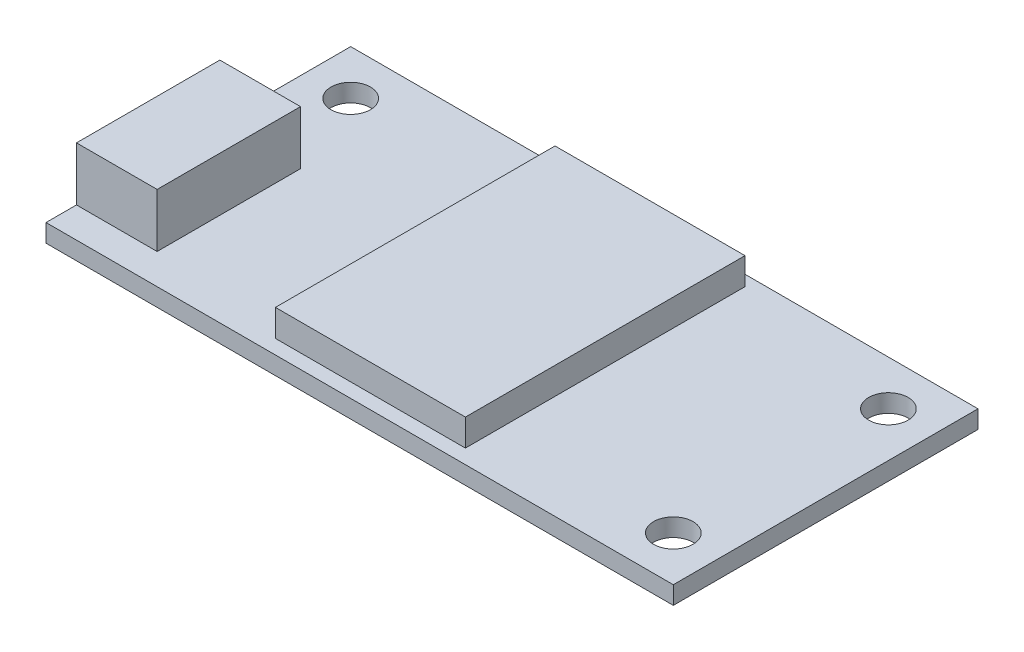
SolidWorks part; units mm, degrees
ref_plane "Front Plane" through (0, 0, 0) normal (0, 0, 1) x (1, 0, 0)
ref_plane "Top Plane" through (0, 0, 0) normal (0, 1, 0) x (1, 0, 0)
ref_plane "Right Plane" through (0, 0, 0) normal (1, 0, 0) x (0, 0, -1)
sketch "Sketch1" plane through (0, 0, 0) normal (0, 1, 0) x (1, 0, 0)
  line L1 (-17.5, -8.5) -> (17.5, -8.5)
  line L2 (-17.5, -8.5) -> (-17.5, 8.5)
  line L3 (-17.5, 8.5) -> (17.5, 8.5)
  line L4 (17.5, -8.5) -> (17.5, 8.5)
  line L5 (-17.5, -8.5) -> (17.5, 8.5) construction
  line L6 (-17.5, 8.5) -> (17.5, -8.5) construction
  point P0 (0, 0)
  dimension "D1" = 17
  dimension "D2" = 35
extrude "Boss-Extrude1" add sketch "Sketch1" along normal mid plane 1
sketch "Sketch2" plane through (0, 0.5, 0) normal (0, 1, 0) x (1, 0, 0)
  line L0 (-17.5, 8.5) -> (-17.5, -8.5) construction
  line L1 (-17.5, -6.8) -> (-13, -6.8)
  line L2 (-17.5, -6.8) -> (-17.5, 1.2)
  line L3 (-17.5, 1.2) -> (-13, 1.2)
  line L4 (-13, -6.8) -> (-13, 1.2)
  line L7 (17.5, 8.5) -> (-17.5, 8.5) construction
  dimension "D1" = 8
  dimension "D2" = 7.3
  dimension "D3" = 4.5
extrude "Boss-Extrude2" add sketch "Sketch2" along normal blind 3
sketch "Sketch3" plane through (0, 0.5, 0) normal (0, 1, 0) x (1, 0, 0)
  line L0 (-17.5, -8.5) -> (17.5, -8.5) construction
  line L1 (-5.5, -7.7) -> (5.1, -7.7)
  line L2 (-5.5, -7.7) -> (-5.5, 7.9)
  line L3 (-5.5, 7.9) -> (5.1, 7.9)
  line L4 (5.1, -7.7) -> (5.1, 7.9)
  line L5 (-17.5, 8.5) -> (-17.5, 1.2) construction
  dimension "D1" = 15.6
  dimension "D2" = 10.6
  dimension "D3" = 0.8
  dimension "D4" = 22.6
extrude "Boss-Extrude3" add sketch "Sketch3" along normal blind 1.5
sketch "Sketch4" plane through (0, 0.5, 0) normal (0, 1, 0) x (1, 0, 0)
  line L0 (-15, 6) -> (15, 6) construction
  line L1 (15, 6) -> (15, -6) construction
  line L2 (17.5, 0) -> (-17.5, 0) construction
  line L3 (17.5, -8.5) -> (17.5, 8.5) construction
  line L4 (-17.5, 1.2) -> (-17.5, -6.8) construction
  line L7 (-17.5, -8.5) -> (17.5, -8.5) construction
  line L8 (17.5, 8.5) -> (-17.5, 8.5) construction
  line L9 (-17.5, 8.5) -> (-17.5, 1.2) construction
  circle A0 centre (15, 6) radius 1.1
  circle A1 centre (15, -6) radius 1.1
  circle A2 centre (-15, 6) radius 1.1
  point P6 (0, 0)
  dimension "D2" = 2.2
  dimension "D4" = 2.5
  dimension "D1" = 12
  dimension "D3" = 12
  dimension "D5" = 30
  dimension "D6" = 2.5
  dimension "D7" = 2.5
  dimension "D8" = 2.5
extrude "Cut-Extrude1" cut sketch "Sketch4" against normal through all both and the other way through all
